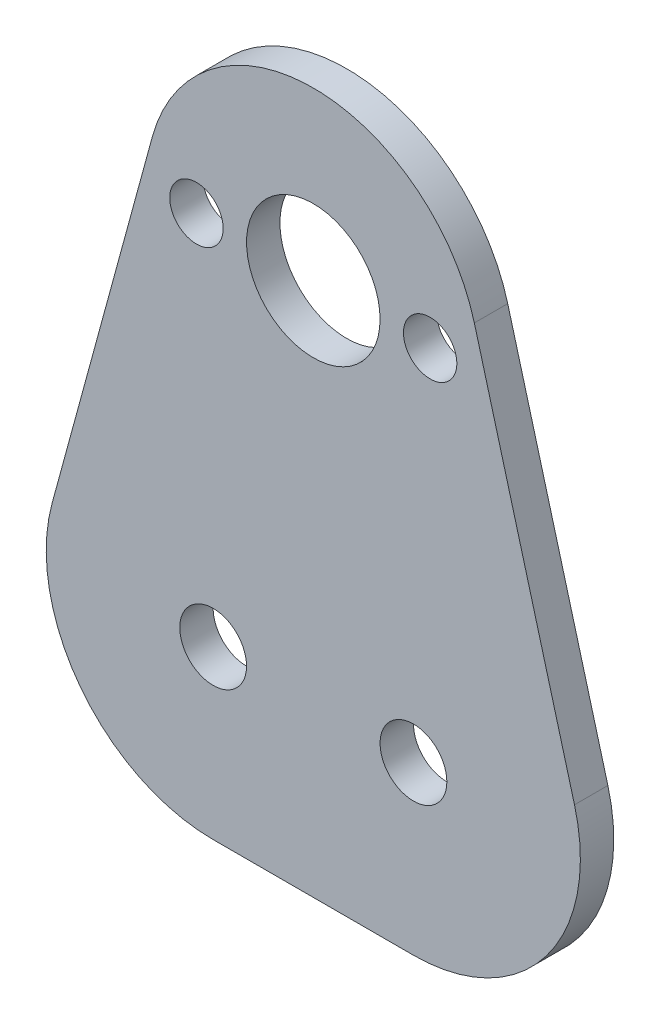
SolidWorks part; units mm, degrees
ref_plane "Front Plane" through (0, 0, 0) normal (0, 0, 1) x (1, 0, 0)
ref_plane "Top Plane" through (0, 0, 0) normal (0, 1, 0) x (1, 0, 0)
ref_plane "Right Plane" through (0, 0, 0) normal (1, 0, 0) x (0, 0, -1)
sketch "Sketch1" plane through (0, 0, 0) normal (0, 0, 1) x (1, 0, 0)
  line L0 (0, 0) -> (0, -55) construction
  line L1 (-15, -55) -> (15, -55) construction
  line L2 (0, 0) -> (-15, -55) construction
  line L3 (0, 0) -> (15, -55) construction
  line L4 (-39.1191, -48.4221) -> (-24.1191, 6.5779)
  line L5 (24.1191, 6.5779) -> (39.1191, -48.4221)
  line L6 (-15, -80) -> (15, -80)
  circle A0 centre (0, 0) radius 10
  circle A1 centre (-15, -55) radius 5
  circle A2 centre (15, -55) radius 5
  arc A3 (24.1191, 6.5779) -> (-24.1191, 6.5779) centre (0, 0) ccw
  arc A4 (-39.1191, -48.4221) -> (-15, -80) centre (-15, -55) ccw
  arc A5 (15, -80) -> (39.1191, -48.4221) centre (15, -55) ccw
  circle A6 centre (0, 0) radius 25 construction
  circle A7 centre (-15, -55) radius 25 construction
  circle A8 centre (15, -55) radius 25 construction
  circle A9 centre (0, 0) radius 25 construction
  point P7 (0, -55)
  point P12 (53.9076, -42.6907)
  point P14 (25, 0)
  point P21 (-6.0924, -42.6907)
  dimension "D1" = 20
  dimension "D4" = 10
  dimension "D2" = 55
  dimension "D3" = 30
  dimension "D5" = 15
extrude "Boss-Extrude2" add sketch "Sketch1" along normal mid plane 5
sketch "Sketch3" plane through (0, 0, 0) normal (0, 0, 1) x (1, 0, 0)
  line L0 (0, 0) -> (0, 10) construction
  line L2 (-4, 14) -> (4, 14) construction
  line L3 (-4, 14) -> (-4, 6) construction
  line L4 (-4, 6) -> (4, 6) construction
  line L5 (4, 14) -> (4, 6) construction
  line L6 (-4, 14) -> (4, 6) construction
  line L7 (-4, 6) -> (4, 14) construction
  circle A0 centre (0, 0) radius 10 construction
  circle A1 centre (0, 0) radius 17.5 construction
  circle A2 centre (17.5, 0) radius 4
  circle A3 centre (-17.5, 0) radius 4
  dimension "D3" = 35
  dimension "D4" = 8
  dimension "D1" = 8
  dimension "D2" = 8
extrude "Cut-Extrude1" cut sketch "Sketch3" against normal through all both and the other way through all
ref_plane "Plane1" through (0, 0, -9.5) normal (0, 0, -1) x (-1, 0, 0)
sketch "Sketch4" plane through (0, 0, -9.5) normal (0, 0, -1) x (-1, 0, 0)
  line L0 (15, -55) -> (-15, -55) construction
  line L1 (0, 0) -> (0, -55) construction
  line L2 (15, -55) -> (-15, -55)
  line L3 (0, 0) -> (0, -55)
